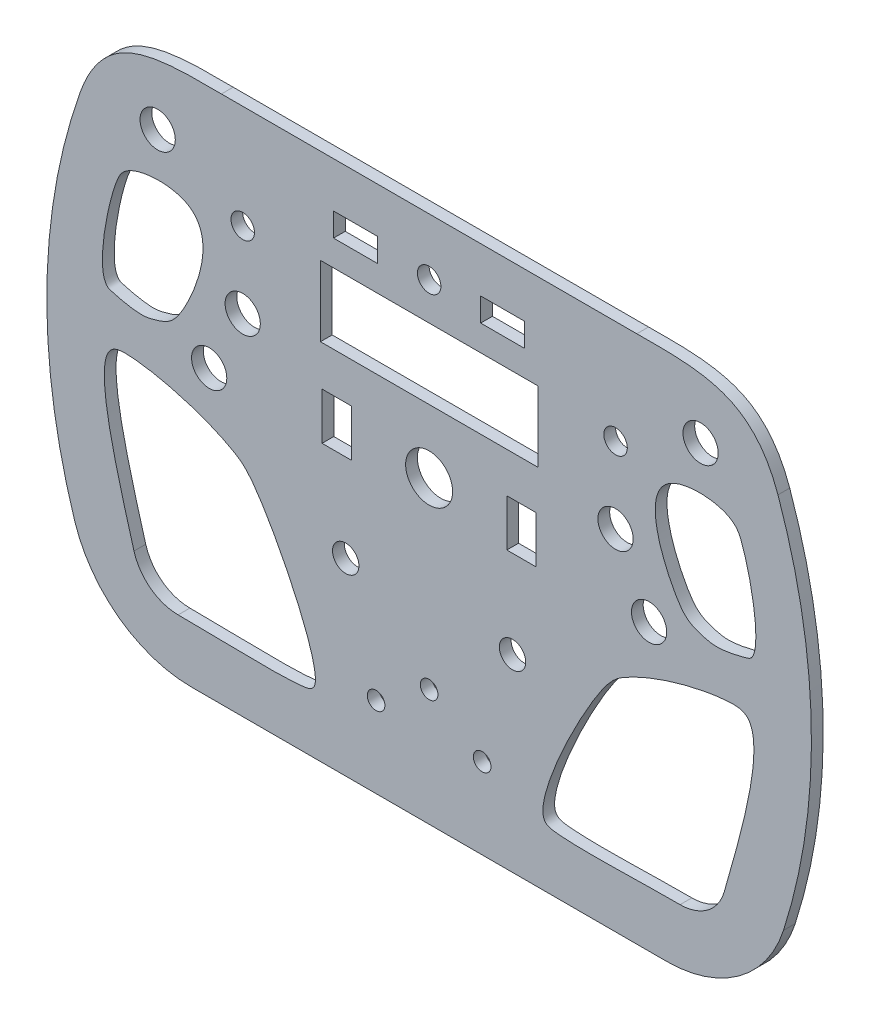
SolidWorks part; units mm, degrees
ref_plane "Front Plane" through (0, 0, 0) normal (0, 0, 1) x (1, 0, 0)
ref_plane "Top Plane" through (0, 0, 0) normal (0, 1, 0) x (1, 0, 0)
ref_plane "Right Plane" through (0, 0, 0) normal (1, 0, 0) x (0, 0, -1)
sketch "Boundary" plane through (0, 0, 0) normal (0, 0, 1) x (1, 0, 0)
  line L1 (-130.175, 100) -> (130.175, 100)
  line L2 (-130.175, 100) -> (-130.175, -100)
  line L3 (-130.175, -100) -> (130.175, -100)
  line L4 (130.175, 100) -> (130.175, -100)
  line L5 (0, -100) -> (0, 100) construction
  line L6 (-130.175, 0) -> (130.175, 0) construction
  point P0 (0, 0)
  dimension "D1" = 260.35
  dimension "D2" = 200
sketch "Frame" plane through (0, 0, 0) normal (0, 0, 1) x (1, 0, 0)
  line L0 (70.7159, 90) -> (-70.7159, 90)
  line L1 (0, -100) -> (0, 100) construction
  line L2 (80.8823, -90) -> (-80.8823, -90)
  line L3 (-130.175, 0) -> (130.175, 0) construction
  line L4 (0, -100) -> (0, 100) construction
  line L6 (-130.175, 100) -> (-130.175, -100) construction
  arc A0 (-118.7831, 66.5357) -> (-120.655, -60.9702) centre (69.825, 0) ccw
  arc A1 (-120.655, -60.9702) -> (-80.8823, -90) centre (-80.8823, -48.2395) ccw
  arc A2 (120.655, -60.9702) -> (80.8823, -90) centre (80.8823, -48.2395) cw
  arc A3 (118.7831, 66.5357) -> (120.655, -60.9702) centre (-69.825, 0) cw
  spline S0 degree 3 poles (-118.7831, 66.5357) (-115.6402, 75.4447) (-104.0419, 90.9949) (-81.0415, 90) (-70.7159, 90) knots 0 0 0 0 0.418855 1 1 1 1
  spline S1 degree 3 poles (118.7831, 66.5357) (115.6402, 75.4447) (104.0419, 90.9949) (81.0415, 90) (70.7159, 90) knots 0 0 0 0 0.418855 1 1 1 1
  point P10 (0, 90)
  point P20 (0, -90)
  dimension "D3" = 200
  dimension "D1" = 90
  dimension "D2" = 90
sketch "Grip Holes" plane through (0, 0, 0) normal (0, 0, 1) x (1, 0, 0)
  line L0 (0, -100) -> (0, 100) construction
  line L1 (0, -100) -> (0, 100) construction
  arc A0 (-100.4905, -59.664) -> (-85.4534, -70.9698) centre (-85.5083, -55.3901) ccw
  arc A2 (100.4905, -59.664) -> (85.4534, -70.9698) centre (85.5083, -55.3901) cw
  spline S0 degree 3 poles (-106.1741, 12.498) (-114.0432, 14.9767) (-108.9403, 41.9057) (-102.6075, 54.1938) (-69.7861, 55.9372) (-78.8834, 28.7082) (-86.5038, 14.9652) (-89.4525, 12.907) (-98.8906, 10.7258) (-106.1741, 12.498) (-114.0432, 14.9767) (-108.9403, 41.9057) knots -0.134424 -0.10189 -0.011321 0 0.195913 0.234751 0.388384 0.646034 0.695875 0.865576 0.89811 0.988679 1 1.195913 1.234751 1.388384 only from (-109.1364, 13.5028) to (-109.1364, 13.5028)
  spline S1 degree 3 poles (-100.4905, -59.664) (-106.3432, -39.1471) (-116.8749, -2.9799) (-94.6893, -2.513) (-72.0638, -9.126) (-56.9745, -20.0037) (-32.6318, -69.036) (-49.0089, -72.0899) (-71.3474, -70.9201) (-85.4534, -70.9698) knots 0 0 0 0 0.257067 0.314961 0.549603 0.600127 0.769678 0.811785 1 1 1 1
  spline S2 degree 3 poles (100.4905, -59.664) (106.3432, -39.1471) (116.8749, -2.9799) (94.6893, -2.513) (72.0638, -9.126) (56.9745, -20.0037) (32.6318, -69.036) (49.0089, -72.0899) (71.3474, -70.9201) (85.4534, -70.9698) knots 0 0 0 0 0.257067 0.314961 0.549603 0.600127 0.769678 0.811785 1 1 1 1
  spline S3 degree 3 poles (106.1741, 12.498) (114.0432, 14.9767) (108.9403, 41.9057) (102.6075, 54.1938) (69.7861, 55.9372) (78.8834, 28.7082) (86.5038, 14.9652) (89.4525, 12.907) (98.8906, 10.7258) (106.1741, 12.498) (114.0432, 14.9767) (108.9403, 41.9057) knots -0.134424 -0.10189 -0.011321 0 0.195913 0.234751 0.388384 0.646034 0.695875 0.865576 0.89811 0.988679 1 1.195913 1.234751 1.388384 only from (109.1364, 13.5028) to (109.1364, 13.5028)
sketch "Feature Holes" plane through (0, 0, 0) normal (0, 0, 1) x (1, 0, 0)
  line L0 (0, -100) -> (0, 100) construction
  line L1 (-37, 57.7983) -> (37, 57.7983)
  line L2 (-37, 57.7983) -> (-37, 33.7983)
  line L3 (-37, 33.7983) -> (37, 33.7983)
  line L4 (37, 57.7983) -> (37, 33.7983)
  line L5 (0, 33.7983) -> (0, 57.7983) construction
  line L6 (-37, 45.7983) -> (37, 45.7983) construction
  line L7 (0, -100) -> (0, 100) construction
  line L8 (-32.5568, 74.5767) -> (-17.5568, 74.5767)
  line L9 (-32.5568, 74.5767) -> (-32.5568, 66.5767)
  line L10 (-32.5568, 66.5767) -> (-17.5568, 66.5767)
  line L11 (-17.5568, 74.5767) -> (-17.5568, 66.5767)
  line L12 (-25.0568, 66.5767) -> (-25.0568, 74.5767) construction
  line L13 (-32.5568, 70.5767) -> (-17.5568, 70.5767) construction
  line L14 (36.4602, 12.1108) -> (26.4602, 12.1108) construction
  line L15 (-36.4602, 20.1108) -> (-26.4602, 20.1108)
  line L16 (-36.4602, 20.1108) -> (-36.4602, 4.1108)
  line L17 (-36.4602, 4.1108) -> (-26.4602, 4.1108)
  line L18 (-26.4602, 20.1108) -> (-26.4602, 4.1108)
  line L19 (-31.4602, 4.1108) -> (-31.4602, 20.1108) construction
  line L20 (-36.4602, 12.1108) -> (-26.4602, 12.1108) construction
  line L21 (31.4602, 4.1108) -> (31.4602, 20.1108) construction
  line L22 (26.4602, 20.1108) -> (26.4602, 4.1108)
  line L23 (36.4602, 4.1108) -> (26.4602, 4.1108)
  line L24 (36.4602, 20.1108) -> (36.4602, 4.1108)
  line L25 (36.4602, 20.1108) -> (26.4602, 20.1108)
  line L26 (32.5568, 70.5767) -> (17.5568, 70.5767) construction
  line L27 (25.0568, 66.5767) -> (25.0568, 74.5767) construction
  line L28 (17.5568, 74.5767) -> (17.5568, 66.5767)
  line L29 (32.5568, 66.5767) -> (17.5568, 66.5767)
  line L30 (32.5568, 74.5767) -> (32.5568, 66.5767)
  line L31 (32.5568, 74.5767) -> (17.5568, 74.5767)
  circle A0 centre (-74.892, 7.0994) radius 6
  circle A1 centre (-63.4773, 28.8153) radius 6
  circle A2 centre (0, 70.5767) radius 4
  circle A3 centre (-63.4773, 54.7074) radius 4
  circle A4 centre (-92.4318, 68.6278) radius 6
  circle A5 centre (-28.3977, -25.7528) radius 4.5
  circle A6 centre (-28.3977, -25.7528) radius 12.5 construction
  circle A7 centre (0, 12.1108) radius 8
  circle A8 centre (-18.0559, -62.5028) radius 3
  circle A9 centre (0, -50.2528) radius 3
  circle A10 centre (28.3977, -25.7528) radius 12.5 construction
  circle A11 centre (18.0559, -62.5028) radius 3
  circle A12 centre (28.3977, -25.7528) radius 4.5
  circle A13 centre (63.4773, 54.7074) radius 4
  circle A14 centre (92.4318, 68.6278) radius 6
  circle A15 centre (63.4773, 28.8153) radius 6
  circle A16 centre (74.892, 7.0994) radius 6
  point P2 (0, 45.7983)
  point P17 (-25.0568, 70.5767)
  point P51 (-31.4602, 12.1108)
  point P61 (31.4602, 12.1108)
  point P74 (25.0568, 70.5767)
  dimension "D1" = 12
  dimension "D2" = 12
  dimension "D5" = 8
  dimension "D6" = 8
  dimension "D7" = 12
  dimension "D10" = 9
  dimension "D11" = 25
  dimension "D12" = 16
  dimension "D13" = 6
  dimension "D14" = 6
  dimension "D3" = 74
  dimension "D4" = 24
  dimension "D8" = 15
  dimension "D9" = 8
  dimension "D15" = 16
  dimension "D16" = 10
sketch "PCB Spacing" plane through (0, 0, 0) normal (0, 0, 1) x (1, 0, 0)
  line L0 (0, -100) -> (0, 100) construction
  line L1 (-45, 79.1278) -> (45, 79.1278)
  line L2 (-45, 79.1278) -> (-45, -20.8722)
  line L3 (-45, -20.8722) -> (45, -20.8722)
  line L4 (45, 79.1278) -> (45, -20.8722)
  line L5 (0, -20.8722) -> (0, 79.1278) construction
  line L6 (-45, 29.1278) -> (45, 29.1278) construction
  line L7 (-45, -20.8722) -> (-34, -53.8722)
  line L8 (-34, -53.8722) -> (34, -53.8722)
  line L9 (0, -100) -> (0, 100) construction
  line L10 (45, -20.8722) -> (34, -53.8722)
  point P0 (0, 29.1278)
  point P9 (0, -53.8722)
  dimension "D1" = 90
  dimension "D2" = 100
  dimension "D3" = 68
  dimension "D4" = 33
  dimension "D5" = 108.435
sketch "Combine Sketch" plane through (0, 0, 0) normal (0, 0, 1) x (1, 0, 0)
  line L2 (70.7159, 90) -> (-70.7159, 90)
  line L3 (-80.8823, -90) -> (80.8823, -90)
  line L4 (70.7159, 90) -> (-70.7159, 90)
  line L5 (-80.8823, -90) -> (80.8823, -90)
  line L8 (-17.5568, 74.5767) -> (-32.5568, 74.5767)
  line L9 (-32.5568, 74.5767) -> (-32.5568, 66.5767)
  line L10 (-32.5568, 66.5767) -> (-17.5568, 66.5767)
  line L11 (-17.5568, 66.5767) -> (-17.5568, 74.5767)
  line L12 (-17.5568, 74.5767) -> (-32.5568, 74.5767)
  line L13 (-32.5568, 74.5767) -> (-32.5568, 66.5767)
  line L14 (-32.5568, 66.5767) -> (-17.5568, 66.5767)
  line L15 (-17.5568, 66.5767) -> (-17.5568, 74.5767)
  line L16 (26.4602, 20.1108) -> (26.4602, 4.1108)
  line L17 (26.4602, 4.1108) -> (36.4602, 4.1108)
  line L18 (36.4602, 4.1108) -> (36.4602, 20.1108)
  line L19 (36.4602, 20.1108) -> (26.4602, 20.1108)
  line L20 (26.4602, 20.1108) -> (26.4602, 4.1108)
  line L21 (26.4602, 4.1108) -> (36.4602, 4.1108)
  line L22 (36.4602, 4.1108) -> (36.4602, 20.1108)
  line L23 (36.4602, 20.1108) -> (26.4602, 20.1108)
  line L24 (-36.4602, 20.1108) -> (-36.4602, 4.1108)
  line L25 (-36.4602, 4.1108) -> (-26.4602, 4.1108)
  line L26 (-26.4602, 4.1108) -> (-26.4602, 20.1108)
  line L27 (-26.4602, 20.1108) -> (-36.4602, 20.1108)
  line L28 (-36.4602, 20.1108) -> (-36.4602, 4.1108)
  line L29 (-36.4602, 4.1108) -> (-26.4602, 4.1108)
  line L30 (-26.4602, 4.1108) -> (-26.4602, 20.1108)
  line L31 (-26.4602, 20.1108) -> (-36.4602, 20.1108)
  line L32 (17.5568, 74.5767) -> (17.5568, 66.5767)
  line L33 (17.5568, 66.5767) -> (32.5568, 66.5767)
  line L34 (32.5568, 66.5767) -> (32.5568, 74.5767)
  line L35 (32.5568, 74.5767) -> (17.5568, 74.5767)
  line L36 (17.5568, 74.5767) -> (17.5568, 66.5767)
  line L37 (17.5568, 66.5767) -> (32.5568, 66.5767)
  line L38 (32.5568, 66.5767) -> (32.5568, 74.5767)
  line L39 (32.5568, 74.5767) -> (17.5568, 74.5767)
  line L40 (37, 57.7983) -> (-37, 57.7983)
  line L41 (-37, 57.7983) -> (-37, 33.7983)
  line L42 (-37, 33.7983) -> (37, 33.7983)
  line L43 (37, 33.7983) -> (37, 57.7983)
  line L44 (37, 57.7983) -> (-37, 57.7983)
  line L45 (-37, 57.7983) -> (-37, 33.7983)
  line L46 (-37, 33.7983) -> (37, 33.7983)
  line L47 (37, 33.7983) -> (37, 57.7983)
  arc A1 (-100.4905, -59.664) -> (-85.4534, -70.9698) centre (-85.5083, -55.3901) ccw
  arc A2 (-100.4905, -59.664) -> (-85.4534, -70.9698) centre (-85.5083, -55.3901) ccw
  arc A3 (85.4534, -70.9698) -> (100.4905, -59.664) centre (85.5083, -55.3901) ccw
  arc A4 (80.8823, -90) -> (120.655, -60.9702) centre (80.8823, -48.2395) ccw
  arc A5 (120.655, -60.9702) -> (118.7831, 66.5357) centre (-69.825, 0) ccw
  arc A6 (-118.7831, 66.5357) -> (-120.655, -60.9702) centre (69.825, 0) ccw
  arc A7 (-120.655, -60.9702) -> (-80.8823, -90) centre (-80.8823, -48.2395) ccw
  arc A8 (80.8823, -90) -> (120.655, -60.9702) centre (80.8823, -48.2395) ccw
  arc A9 (120.655, -60.9702) -> (118.7831, 66.5357) centre (-69.825, 0) ccw
  arc A10 (-118.7831, 66.5357) -> (-120.655, -60.9702) centre (69.825, 0) ccw
  arc A11 (-120.655, -60.9702) -> (-80.8823, -90) centre (-80.8823, -48.2395) ccw
  arc A12 (85.4534, -70.9698) -> (100.4905, -59.664) centre (85.5083, -55.3901) ccw
  circle A13 centre (-92.4318, 68.6278) radius 6
  circle A14 centre (-92.4318, 68.6278) radius 6
  circle A15 centre (-63.4773, 54.7074) radius 4
  circle A16 centre (-63.4773, 54.7074) radius 4
  circle A17 centre (0, 70.5767) radius 4
  circle A18 centre (0, 70.5767) radius 4
  circle A19 centre (-63.4773, 28.8153) radius 6
  circle A20 centre (-63.4773, 28.8153) radius 6
  circle A21 centre (-74.892, 7.0994) radius 6
  circle A22 centre (-74.892, 7.0994) radius 6
  circle A23 centre (0, -50.2528) radius 3
  circle A24 centre (0, -50.2528) radius 3
  circle A25 centre (-18.0559, -62.5028) radius 3
  circle A26 centre (-18.0559, -62.5028) radius 3
  circle A27 centre (0, 12.1108) radius 8
  circle A28 centre (0, 12.1108) radius 8
  circle A29 centre (-28.3977, -25.7528) radius 4.5
  circle A30 centre (-28.3977, -25.7528) radius 4.5
  circle A31 centre (92.4318, 68.6278) radius 6
  circle A32 centre (92.4318, 68.6278) radius 6
  circle A33 centre (63.4773, 54.7074) radius 4
  circle A34 centre (63.4773, 54.7074) radius 4
  circle A35 centre (28.3977, -25.7528) radius 4.5
  circle A36 centre (28.3977, -25.7528) radius 4.5
  circle A37 centre (18.0559, -62.5028) radius 3
  circle A38 centre (18.0559, -62.5028) radius 3
  circle A39 centre (74.892, 7.0994) radius 6
  circle A40 centre (74.892, 7.0994) radius 6
  circle A41 centre (63.4773, 28.8153) radius 6
  circle A42 centre (63.4773, 28.8153) radius 6
  spline S1 degree 3 poles (-108.9403, 41.9057) (-114.0432, 14.9767) (-106.1741, 12.498) (-98.8906, 10.7258) (-89.4525, 12.907) (-86.5038, 14.9652) (-78.8834, 28.7082) (-69.7861, 55.9372) (-102.6075, 54.1938) (-108.9403, 41.9057) (-114.0432, 14.9767) (-106.1741, 12.498) knots -0.388384 -0.234751 -0.195913 0 0.011321 0.10189 0.134424 0.304125 0.353966 0.611616 0.765249 0.804087 1 1.011321 1.10189 1.134424 only from (-109.1364, 13.5028) to (-109.1364, 13.5028)
  spline S2 degree 3 poles (1534.5807, 2709.0364) (-872.6756, -2031.0724) (759.331, 831.9579) (-271.8045, -169.4303) (2356.8269, 2031.8747) knots -10.382804 -10.382804 -10.382804 -10.382804 0.418855 4.900144 4.900144 4.900144 4.900144 only from (118.7831, 66.5357) to (70.7159, 90)
  spline S3 degree 3 poles (-2356.901, 2031.9368) (271.8102, -169.4358) (-759.3399, 831.9701) (872.6896, -2031.0968) (-1534.6243, 2709.1222) knots -3.900186 -3.900186 -3.900186 -3.900186 0.581145 11.382869 11.382869 11.382869 11.382869 only from (-70.7159, 90) to (-118.7831, 66.5357)
  spline S4 degree 3 poles (118.7831, 66.5357) (115.6402, 75.4447) (104.0419, 90.9949) (81.0415, 90) (70.7159, 90) knots 0 0 0 0 0.418855 1 1 1 1
  spline S5 degree 3 poles (-70.7159, 90) (-81.0415, 90) (-104.0419, 90.9949) (-115.6402, 75.4447) (-118.7831, 66.5357) knots 0 0 0 0 0.581145 1 1 1 1
  spline S6 degree 3 poles (-108.9403, 41.9057) (-114.0432, 14.9767) (-106.1741, 12.498) (-98.8906, 10.7258) (-89.4525, 12.907) (-86.5038, 14.9652) (-78.8834, 28.7082) (-69.7861, 55.9372) (-102.6075, 54.1938) (-108.9403, 41.9057) (-114.0432, 14.9767) (-106.1741, 12.498) knots -0.388384 -0.234751 -0.195913 0 0.011321 0.10189 0.134424 0.304125 0.353966 0.611616 0.765249 0.804087 1 1.011321 1.10189 1.134424 only from (-109.1364, 13.5028) to (-109.1364, 13.5028)
  spline S7 degree 3 poles (2821.6722, -809.4676) (-596.4362, 10.1955) (-95.0268, -80.671) (-32.6318, -69.036) (-56.9745, -20.0037) (-72.0638, -9.126) (-94.6893, -2.513) (-160.3928, -3.8958) (238.098, -707.3353) (-1516.0431, 2585.0254) knots -1.1236 -1.1236 -1.1236 -1.1236 0.188215 0.230322 0.399873 0.450397 0.685039 0.742933 2.078066 2.078066 2.078066 2.078066 only from (-85.4534, -70.9698) to (-100.4905, -59.664)
  spline S8 degree 3 poles (-85.4534, -70.9698) (-71.3474, -70.9201) (-49.0089, -72.0899) (-32.6318, -69.036) (-56.9745, -20.0037) (-72.0638, -9.126) (-94.6893, -2.513) (-116.8749, -2.9799) (-106.3432, -39.1471) (-100.4905, -59.664) knots 0 0 0 0 0.188215 0.230322 0.399873 0.450397 0.685039 0.742933 1 1 1 1
  spline S9 degree 3 poles (106.1741, 12.498) (114.0432, 14.9767) (108.9403, 41.9057) (102.6075, 54.1938) (69.7861, 55.9372) (78.8834, 28.7082) (86.5038, 14.9652) (89.4525, 12.907) (98.8906, 10.7258) (106.1741, 12.498) (114.0432, 14.9767) (108.9403, 41.9057) knots -0.134424 -0.10189 -0.011321 0 0.195913 0.234751 0.388384 0.646034 0.695875 0.865576 0.89811 0.988679 1 1.195913 1.234751 1.388384 only from (109.1364, 13.5028) to (109.1364, 13.5028)
  spline S10 degree 3 poles (106.1741, 12.498) (114.0432, 14.9767) (108.9403, 41.9057) (102.6075, 54.1938) (69.7861, 55.9372) (78.8834, 28.7082) (86.5038, 14.9652) (89.4525, 12.907) (98.8906, 10.7258) (106.1741, 12.498) (114.0432, 14.9767) (108.9403, 41.9057) knots -0.134424 -0.10189 -0.011321 0 0.195913 0.234751 0.388384 0.646034 0.695875 0.865576 0.89811 0.988679 1 1.195913 1.234751 1.388384 only from (109.1364, 13.5028) to (109.1364, 13.5028)
  spline S11 degree 3 poles (1516.0802, 2585.0949) (-238.1034, -707.3448) (160.3931, -3.8958) (94.6893, -2.513) (72.0638, -9.126) (56.9745, -20.0037) (32.6318, -69.036) (95.0273, -80.6711) (596.4461, 10.1973) (-2821.7757, -809.4924) knots -1.078075 -1.078075 -1.078075 -1.078075 0.257067 0.314961 0.549603 0.600127 0.769678 0.811785 2.123613 2.123613 2.123613 2.123613 only from (100.4905, -59.664) to (85.4534, -70.9698)
  spline S12 degree 3 poles (100.4905, -59.664) (106.3432, -39.1471) (116.8749, -2.9799) (94.6893, -2.513) (72.0638, -9.126) (56.9745, -20.0037) (32.6318, -69.036) (49.0089, -72.0899) (71.3474, -70.9201) (85.4534, -70.9698) knots 0 0 0 0 0.257067 0.314961 0.549603 0.600127 0.769678 0.811785 1 1 1 1
  dimension "D1" = 0
  dimension "D2" = 0
  dimension "D3" = 0
  dimension "D4" = 0
  dimension "D5" = 0
  dimension "D6" = 0
  dimension "D7" = 0
  dimension "D8" = 0
  dimension "D9" = 0
  dimension "D10" = 0
  dimension "D11" = 0
  dimension "D12" = 0
  dimension "D13" = 0
  dimension "D14" = 0
  dimension "D15" = 0
  dimension "D16" = 0
  dimension "D17" = 0
  dimension "D18" = 0
  dimension "D19" = 0
  dimension "D20" = 0
  dimension "D21" = 0
  dimension "D22" = 0
  dimension "D23" = 0
  dimension "D24" = 0
  dimension "D25" = 0
extrude "Boss-Extrude1" add sketch "Combine Sketch" along normal blind 4
